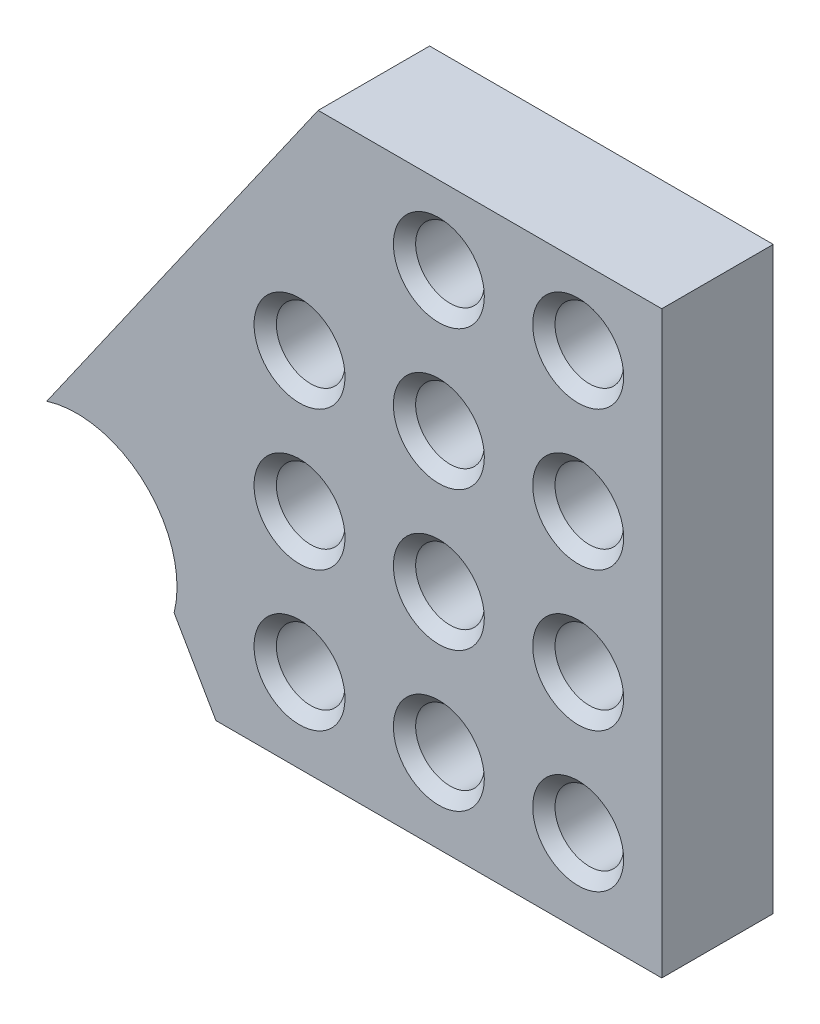
SolidWorks part; units mm, degrees
ref_plane "Front Plane" through (0, 0, 0) normal (0, 0, 1) x (1, 0, 0)
ref_plane "Top Plane" through (0, 0, 0) normal (0, 1, 0) x (1, 0, 0)
ref_plane "Right Plane" through (0, 0, 0) normal (1, 0, 0) x (0, 0, -1)
sketch "Sketch1" plane through (0, 0, 0) normal (0, 0, 1) x (1, 0, 0)
  line L0 (0, 0) -> (0, 33.02)
  line L1 (0, 33.02) -> (-19.5763, 33.02)
  line L2 (-19.5763, 33.02) -> (-35.038, 10.9384)
  line L3 (-27.7812, 4.1244) -> (-25.4, 0)
  line L4 (-25.4, 0) -> (0, 0)
  line L5 (-25.4, 0) -> (-33.2169, 13.5393) construction
  arc A0 (-35.038, 10.9384) -> (-27.7812, 4.1244) centre (-33.3322, 5.484) cw
  circle A1 centre (-33.3322, 5.484) radius 4.1275
  dimension "D1" = 25.4
  dimension "D3" = 5.715
  dimension "D6" = 8.255
  dimension "D2" = 33.02
  dimension "D4" = 4.7625
  dimension "D5" = 120
  dimension "D7" = 3.175
  dimension "D8" = 125
extrude "Boss-Extrude1" add sketch "Sketch1" along normal blind 6.35 contours L5 A0 L3 L4 L0 L1 L2 | A0 L5 L2
hole_wizard "#23 (0.154) Diameter Hole1" positions "3DSketch1" profile "Sketch2" hole size "#23" standard "ANSI Inch" end condition up to next
sketch3d "3DSketch1"
  line L0 (-25.4, 0, 6.35) -> (0, 0, 6.35) construction
  line L1 (0, 0, 6.35) -> (0, 33.02, 6.35) construction
  point P0 (-4.7625, 4.7625, 6.35)
  dimension "D1" = 4.7625
  dimension "D2" = 4.7625
sketch "Sketch2" plane through (-4.7625, 4.7625, 6.35) normal (1, 0, 0) x (0, -1, 0)
  line L0 (0, 0) -> (0, 6.351)
  line L1 (0, 6.351) -> (1.9558, 6.351)
  line L2 (1.9558, 6.351) -> (1.9558, 0.635)
  line L3 (1.9558, 0.635) -> (2.5908, 0)
  line L5 (2.5908, 0) -> (0, 0)
  line L6 (-1.9558, 0.635) -> (-2.5908, 0) construction
  line L11 (0, -6.35) -> (0, 107.95) construction
  dimension "Thru Hole Dia." = 3.9116
  dimension "Thru Hole Depth" = 6.351
  dimension "Near C'Sink Dia." = 5.1816
  dimension "Near C'Sink Angle" = 90
pattern_linear "LPattern1" count 4 spacing 7.9375 along (0, 1, 0) count 3 spacing 7.9375 along (-1, 0, 0) skipping (3, 2) of "#23 (0.154) Diameter Hole1"
